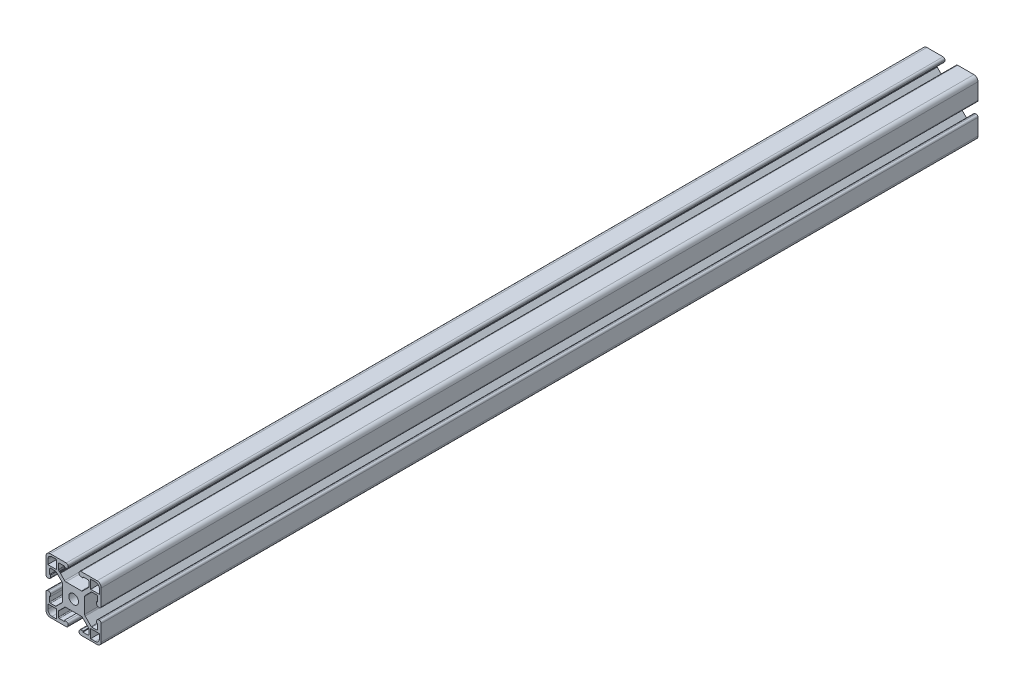
SolidWorks part; units mm, degrees
ref_plane "Front Plane" through (0, 0, 0) normal (0, 0, 1) x (1, 0, 0)
ref_plane "Top Plane" through (0, 0, 0) normal (0, 1, 0) x (1, 0, 0)
ref_plane "Right Plane" through (0, 0, 0) normal (1, 0, 0) x (0, 0, -1)
sketch "Sketch2" plane through (0, 0, 0) normal (0, 0, 1) x (1, 0, 0)
  line L0 (0, 20) -> (0, -20) construction
  line L1 (-20, 0) -> (20, 0) construction
  line L2 (4, -20) -> (20, -20)
  line L3 (20, -20) -> (20, -4)
  line L5 (6.75, -17.36) -> (10.4, -17.36)
  line L7 (0, 0) -> (20, -20) construction
  line L9 (17.36, -6.75) -> (17.36, -10.4)
  line L11 (10.4334, -8.5666) -> (8.5666, -10.4334) construction
  line L12 (11, -16.76) -> (11, -12.8668)
  line L13 (6.1332, -8) -> (11, -12.8668)
  line L14 (16.76, -11) -> (12.8668, -11)
  line L15 (8, -6.1332) -> (12.8668, -11)
  line L16 (4, -20) -> (4, -16.7)
  line L18 (4, -16.7) -> (6.75, -16.7)
  line L19 (6.75, -16.7) -> (6.75, -17.36)
  line L20 (20, -4) -> (16.7, -4)
  line L21 (16.7, -4) -> (16.7, -6.75)
  line L22 (16.7, -6.75) -> (17.36, -6.75)
  line L23 (6.75, -17.36) -> (6.75, -20) construction
  circle A0 centre (0, 0) radius 3.5
  arc A1 (10.4, -17.36) -> (11, -16.76) centre (10.4, -16.76) ccw
  arc A2 (17.36, -10.4) -> (16.76, -11) centre (16.76, -10.4) cw
  point P8 (0, -8)
  point P16 (9.5, -9.5)
  dimension "Center Hole Diameter" = 7
  dimension "D3" = 0.6
  dimension "Rail Height" = 40
  dimension "Rail Width" = 40
  dimension "T-Slot Width" = 8
  dimension "Slot Depth" = 12
  dimension "Inner Slot Width" = 22
  dimension "D1" = 2.75
  dimension "D2" = 3.3
  dimension "D4" = 0.66
sketch "Sketch3" plane through (0, 0, 0) normal (1, 0, 0) x (0, 0, -1)
  line L0 (-317.5, -20) -> (317.5, -20) construction
  line L1 (-292.1, 0) -> (292.1, 0) construction
  dimension "Length" = 635
  dimension "D1" = 25.4
sketch "Sketch4" plane through (0, 0, 0) normal (0, 0, 1) x (1, 0, 0)
  line L1 (20, -17) -> (20, -5.32)
  line L2 (20, -4) -> (16.7, -4) construction
  line L3 (16.7, -4) -> (16.7, -6.75) construction
  line L7 (18.02, -4) -> (18.68, -4)
  line L9 (16.7, -5.32) -> (16.7, -6.75)
  line L10 (16.7, -6.75) -> (17.36, -6.75)
  line L11 (17.36, -6.75) -> (17.36, -10.4)
  line L13 (16.76, -11) -> (13.1153, -11)
  line L18 (16.76, -11) -> (12.8668, -11) construction
  line L20 (8, -6.1332) -> (12.8668, -11) construction
  line L22 (4, -20) -> (20, -20) construction
  line L23 (20, -20) -> (20, -4) construction
  line L24 (17, -20) -> (5.32, -20)
  line L25 (4, -18.02) -> (4, -18.68)
  line L26 (4, -20) -> (4, -16.7) construction
  line L27 (4, -16.7) -> (6.75, -16.7) construction
  line L28 (5.32, -16.7) -> (6.75, -16.7)
  line L29 (6.75, -16.7) -> (6.75, -17.36)
  line L30 (6.75, -17.36) -> (10.4, -17.36)
  line L31 (6.1332, -8) -> (11, -12.8668) construction
  line L32 (11, -16.76) -> (11, -12.8668) construction
  line L33 (11, -13.1153) -> (11, -16.76)
  line L34 (0, -8) -> (5.5865, -8)
  line L35 (6.5199, -8.3866) -> (10.8243, -12.691)
  line L36 (12.691, -10.8243) -> (8.3866, -6.5199)
  line L37 (8, 0) -> (8, -5.5865)
  line L38 (-20, 0) -> (20, 0) construction
  line L39 (15.68, -18.68) -> (12.32, -18.68)
  line L40 (12.32, -18.68) -> (12.32, -12.32)
  line L41 (18.68, -12.32) -> (18.68, -15.68)
  line L42 (12.32, -12.32) -> (18.68, -12.32)
  line L43 (0, 0) -> (20, -20) construction
  line L44 (12.32, -18.68) -> (12.32, -20) construction
  line L45 (11, -14.9376) -> (12.32, -14.9376) construction
  line L46 (0, -8) -> (0, -3.5)
  line L47 (8, 0) -> (3.5, 0)
  arc A1 (18.68, -4) -> (20, -5.32) centre (18.68, -5.32) cw
  arc A10 (16.7, -5.32) -> (18.02, -4) centre (18.02, -5.32) cw
  arc A12 (17, -20) -> (20, -17) centre (17, -17) ccw
  arc A13 (4, -18.02) -> (5.32, -16.7) centre (5.32, -18.02) cw
  arc A14 (4, -18.68) -> (5.32, -20) centre (5.32, -18.68) ccw
  arc A15 (10.4, -17.36) -> (11, -16.76) centre (10.4, -16.76) ccw construction
  arc A16 (10.4, -17.36) -> (11, -16.76) centre (10.4, -16.76) ccw
  arc A17 (10.8243, -12.691) -> (11, -13.1153) centre (10.4, -13.1153) cw
  arc A18 (5.5865, -8) -> (6.5199, -8.3866) centre (5.5865, -9.32) cw
  arc A19 (16.76, -11) -> (17.36, -10.4) centre (16.76, -10.4) ccw construction
  arc A20 (16.76, -11) -> (17.36, -10.4) centre (16.76, -10.4) ccw
  arc A21 (12.691, -10.8243) -> (13.1153, -11) centre (13.1153, -10.4) ccw
  arc A22 (8, -5.5865) -> (8.3866, -6.5199) centre (9.32, -5.5865) ccw
  arc A23 (18.68, -15.68) -> (15.68, -18.68) centre (15.68, -15.68) cw
  circle A24 centre (0, 0) radius 3.5 construction
  arc A25 (0, -3.5) -> (3.5, 0) centre (0, 0) ccw
  point P74 (4, -18.35)
  dimension "D2" = 1.32
  dimension "D1" = 1.32
  dimension "D3" = 3
  dimension "D4" = 3
extrude "Boss-Extrude1" add sketch "Sketch4" along normal mid plane 635
mirror "Mirror1" about plane through (0, 0, 0) normal (1, 0, 0) of bodies 134
mirror "Mirror2" about plane through (0, 0, 0) normal (0, 1, 0) of bodies 135
sketch "Sketch5" plane through (0, 0, 0) normal (0, 0, 1) x (1, 0, 0)
  line L1 (-10.4532, 12.32) -> (-10.4532, 11.99)
  line L2 (-6.5199, 8.3866) -> (-10.8243, 12.691) construction
  line L3 (-10.4532, 11.99) -> (-10.1232, 11.99)
  line L4 (-10.1232, 11.99) -> (-9.8899, 11.7567)
  line L5 (-9.8899, 11.7567) -> (-9.8899, 11.4267)
  line L6 (-9.8899, 11.4267) -> (-9.5599, 11.4267)
  line L7 (-10.4532, 12.32) -> (-9.5599, 12.32)
  line L8 (-9.5599, 12.32) -> (-9.5599, 11.4267)
  dimension "D1" = 0.33
extrude "Cut-Extrude1" cut sketch "Sketch5" against normal through all both and the other way through all
equation "\"D3@Sketch2\"=\"T-Slot Width@Sketch2\"*0.075"
equation "\"D1@Boss-Extrude1\"=\"Length@Sketch3\""
equation "\"D1@Sketch2\"=\"Inner Slot Width@Sketch2\"*0.125"
equation "\"D2@Sketch2\"=\"Slot Depth@Sketch2\"*0.275"
equation "\"D4@Sketch2\"=\"D2@Sketch2\"*0.2"
equation "\"D1@Sketch4\"=\"D2@Sketch2\"*0.4"
equation "\"D2@Sketch4\"=\"D1@Sketch4\""
equation "\"D3@Sketch4\"=\"Rail Height@Sketch2\"*0.075"
equation "\"D4@Sketch4\"=\"Rail Height@Sketch2\"*0.075"
equation "\"D1@Sketch5\"=\"D4@Sketch2\"*0.5"
